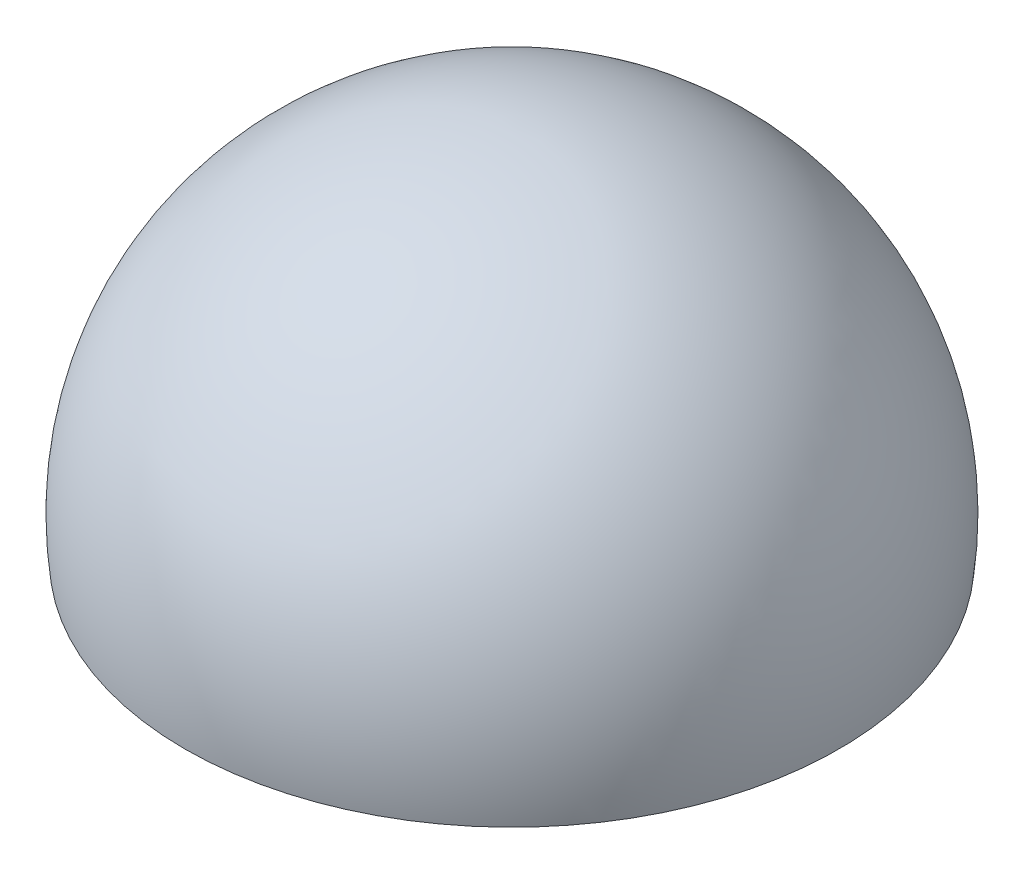
SolidWorks part; units mm, degrees
ref_plane "Front Plane" through (0, 0, 0) normal (0, 0, 1) x (1, 0, 0)
ref_plane "Top Plane" through (0, 0, 0) normal (0, 1, 0) x (1, 0, 0)
ref_plane "Right Plane" through (0, 0, 0) normal (1, 0, 0) x (0, 0, -1)
sketch "Sketch3" plane through (0, 0, 0) normal (1, 0, 0) x (0, 0, -1)
  line L0 (0, 0) -> (7.5, 0)
  line L1 (0, 0) -> (0, 8.5)
  arc A0 (0, 8.5) -> (7.5, 0) centre (0, 0.9412) cw
  dimension "D1" = 7.5
  dimension "D2" = 8.5
revolve "Revolve1" add sketch "Sketch3" angle 360 about L1
sketch "Sketch4" plane through (0, 0, 0) normal (1, 0, 0) x (0, 0, -1)
  line L1 (-7.5, 0) -> (7.5, 0) construction
  line L2 (2.55, 0) -> (2.55, 2)
  line L3 (0, 0) -> (0, 7)
  line L4 (0, 7) -> (-4.5196, 7) construction
  line L6 (0, 0) -> (2.55, 0)
  line L7 (0, 0) -> (0, -2.3756) construction
  arc A0 (2.55, 2) -> (0, 7) centre (0, 3.8498) ccw
  arc A1 (7.5, 0) -> (-7.5, 0) centre (0, 0.9412) ccw construction
  dimension "D1" = 2.55
  dimension "D2" = 2
  dimension "D3" = 7
revolve "Cut-Revolve1" cut sketch "Sketch4" angle 360 about L7
